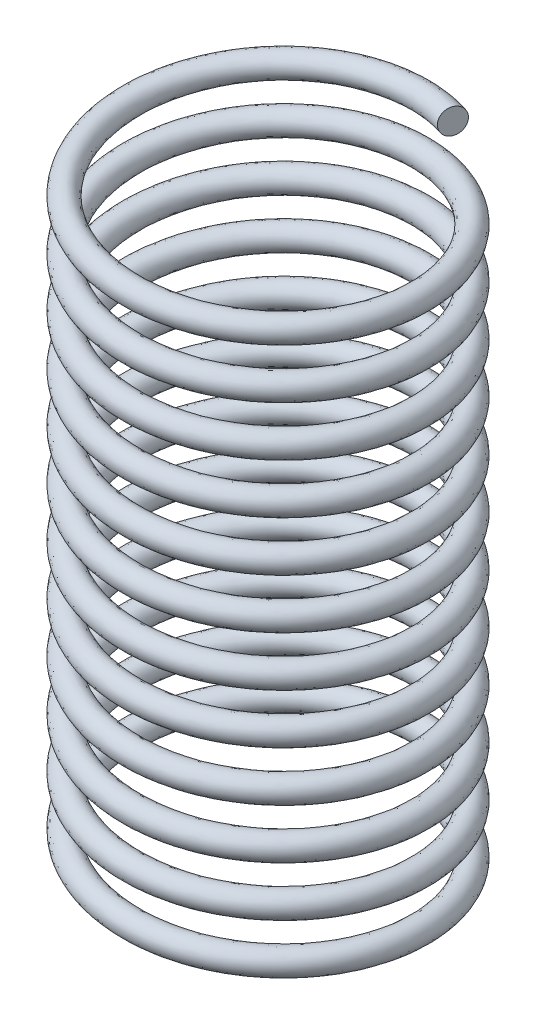
SolidWorks part; units mm, degrees
ref_plane "Front Plane" through (0, 0, 0) normal (0, 0, 1) x (1, 0, 0)
ref_plane "Top Plane" through (0, 0, 0) normal (0, 1, 0) x (1, 0, 0)
ref_plane "Right Plane" through (0, 0, 0) normal (1, 0, 0) x (0, 0, -1)
sketch "Sketch1" plane through (0, 0, 0) normal (0, 1, 0) x (1, 0, 0)
  circle A0 centre (0, 0) radius 12.5
  dimension "D1" = 25
curve "Helix/Spiral1" pitch 4.3167 height 51.8 turns 12
sweep "Sweep1" add path "Helix/Spiral1" circular profile diameter 2.1 parameters "D3"=2.1
